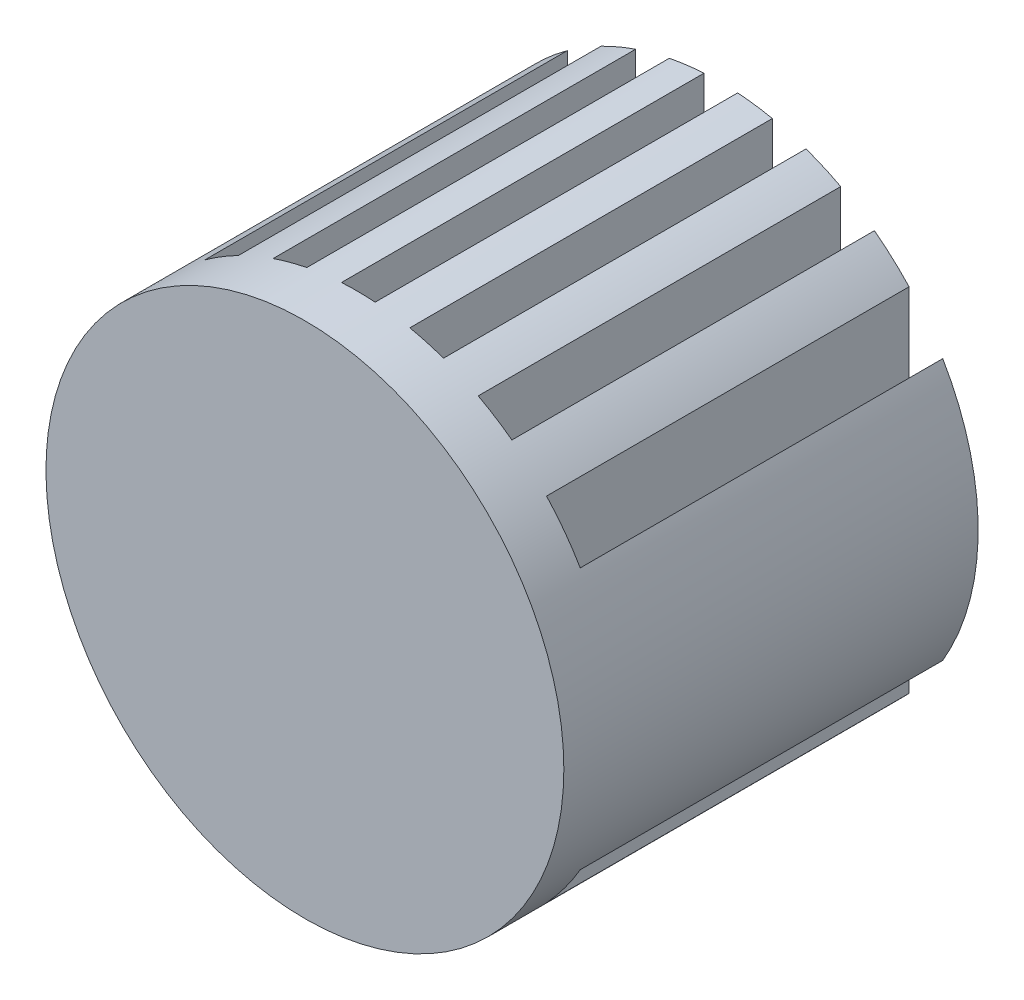
SolidWorks part; units mm, degrees
ref_plane "Plan de face" through (0, 0, 0) normal (0, 0, 1) x (1, 0, 0)
ref_plane "Plan de dessus" through (0, 0, 0) normal (0, 1, 0) x (1, 0, 0)
ref_plane "Plan de droite" through (0, 0, 0) normal (1, 0, 0) x (0, 0, -1)
sketch "Esquisse1" plane through (0, 0, 0) normal (0, 0, 1) x (1, 0, 0)
  circle A0 centre (0, 0) radius 31.75
extrude "Boss.-Extru.1" add sketch "Esquisse1" along normal blind 50.8
sketch "Esquisse3" plane through (0, 0, 0) normal (0, 0, -1) x (-1, 0, 0)
  line L0 (-19.0271, 31.75) -> (-19.0271, -31.75)
  line L1 (-27.4091, 31.75) -> (-23.2791, 31.75)
  line L2 (-27.4091, 31.75) -> (-27.4091, -31.75)
  line L3 (-27.4091, -31.75) -> (-23.2791, -31.75)
  line L4 (-23.2791, 31.75) -> (-23.2791, -31.75)
  line L5 (-19.0271, 31.75) -> (-14.8971, 31.75)
  line L6 (-14.8971, 31.75) -> (-14.8971, -31.75)
  line L7 (-19.0271, -31.75) -> (-14.8971, -31.75)
  line L8 (-10.6451, 31.75) -> (-10.6451, -31.75)
  line L9 (-10.6451, 31.75) -> (-6.5151, 31.75)
  line L10 (-6.5151, 31.75) -> (-6.5151, -31.75)
  line L11 (-10.6451, -31.75) -> (-6.5151, -31.75)
  line L12 (-2.2631, 31.75) -> (-2.2631, -31.75)
  line L13 (-2.2631, 31.75) -> (1.8669, 31.75)
  line L14 (1.8669, 31.75) -> (1.8669, -31.75)
  line L15 (-2.2631, -31.75) -> (1.8669, -31.75)
  line L16 (6.1189, 31.75) -> (6.1189, -31.75)
  line L17 (6.1189, 31.75) -> (10.2489, 31.75)
  line L18 (10.2489, 31.75) -> (10.2489, -31.75)
  line L19 (6.1189, -31.75) -> (10.2489, -31.75)
  line L20 (14.5009, 31.75) -> (14.5009, -31.75)
  line L21 (14.5009, 31.75) -> (18.6309, 31.75)
  line L22 (18.6309, 31.75) -> (18.6309, -31.75)
  line L23 (14.5009, -31.75) -> (18.6309, -31.75)
  line L24 (22.8829, 31.75) -> (22.8829, -31.75)
  line L25 (22.8829, 31.75) -> (27.0129, 31.75)
  line L26 (27.0129, 31.75) -> (27.0129, -31.75)
  line L27 (22.8829, -31.75) -> (27.0129, -31.75)
extrude "Enlèv. mat.-Extru.1" cut sketch "Esquisse3" against normal blind 44.45
